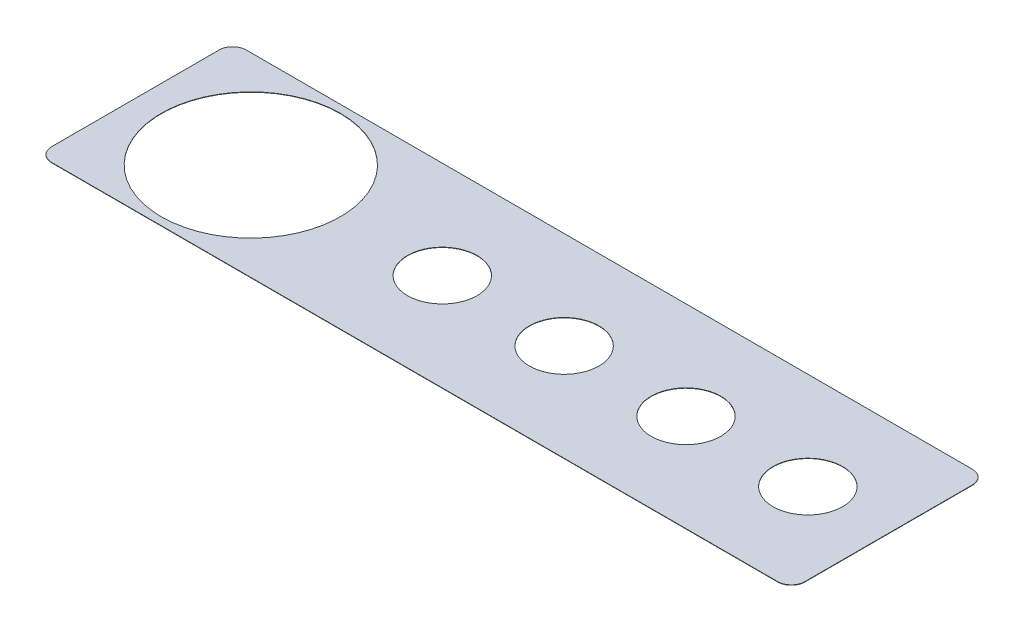
SolidWorks part; units mm, degrees
ref_plane "Front Plane" through (0, 0, 0) normal (0, 0, 1) x (1, 0, 0)
ref_plane "Top Plane" through (0, 0, 0) normal (0, 1, 0) x (1, 0, 0)
ref_plane "Right Plane" through (0, 0, 0) normal (1, 0, 0) x (0, 0, -1)
sketch "Sketch1" plane through (0, 0, 0) normal (0, 1, 0) x (1, 0, 0)
  line L24 (-76.7058, 6.6283) -> (-76.7058, -41.4914)
  line L25 (-72.8058, -45.3914) -> (135.7798, -45.3914)
  line L26 (139.6798, -41.4914) -> (139.6798, 6.6283)
  line L27 (135.7798, 10.5283) -> (-72.8058, 10.5283)
  line L28 (-76.7058, 6.6283) -> (-76.7058, -41.4914)
  line L29 (-72.8058, -45.3914) -> (135.7798, -45.3914)
  line L30 (139.6798, -41.4914) -> (139.6798, 6.6283)
  line L31 (135.7798, 10.5283) -> (-72.8058, 10.5283)
  circle A8 centre (-43.538, -17.4315) radius 25.7363
  arc A21 (-72.8058, 10.5283) -> (-76.7058, 6.6283) centre (-72.8058, 6.6283) ccw
  arc A22 (-76.7058, -41.4914) -> (-72.8058, -45.3914) centre (-72.8058, -41.4914) ccw
  arc A23 (135.7798, -45.3914) -> (139.6798, -41.4914) centre (135.7798, -41.4914) ccw
  arc A24 (139.6798, 6.6283) -> (135.7798, 10.5283) centre (135.7798, 6.6283) ccw
  arc A25 (-72.8058, 10.5283) -> (-76.7058, 6.6283) centre (-72.8058, 6.6283) ccw
  arc A26 (-76.7058, -41.4914) -> (-72.8058, -45.3914) centre (-72.8058, -41.4914) ccw
  arc A27 (135.7798, -45.3914) -> (139.6798, -41.4914) centre (135.7798, -41.4914) ccw
  arc A28 (139.6798, 6.6283) -> (135.7798, 10.5283) centre (135.7798, 6.6283) ccw
  circle A41 centre (-43.538, -17.4315) radius 25.7363 construction
  dimension "D1" = 0.1
extrude "Boss-Extrude1" add sketch "Sketch1" along normal blind 0.1
sketch "Sketch2" plane through (0, 0.1, 0) normal (0, 1, 0) x (1, 0, 0)
  circle A0 centre (11.462, -17.4315) radius 10
  circle A1 centre (46.462, -17.4315) radius 10
  circle A2 centre (81.462, -17.4315) radius 10
  circle A3 centre (116.462, -17.4315) radius 10
  circle A4 centre (11.462, -17.4315) radius 13.625 construction
  circle A5 centre (46.462, -17.4315) radius 13.625 construction
  circle A6 centre (81.462, -17.4315) radius 13.625 construction
  circle A7 centre (116.462, -17.4315) radius 13.625 construction
  dimension "D1" = 20
  dimension "D2" = 27.25
extrude "Cut-Extrude1" cut sketch "Sketch2" against normal through all both and the other way through all
